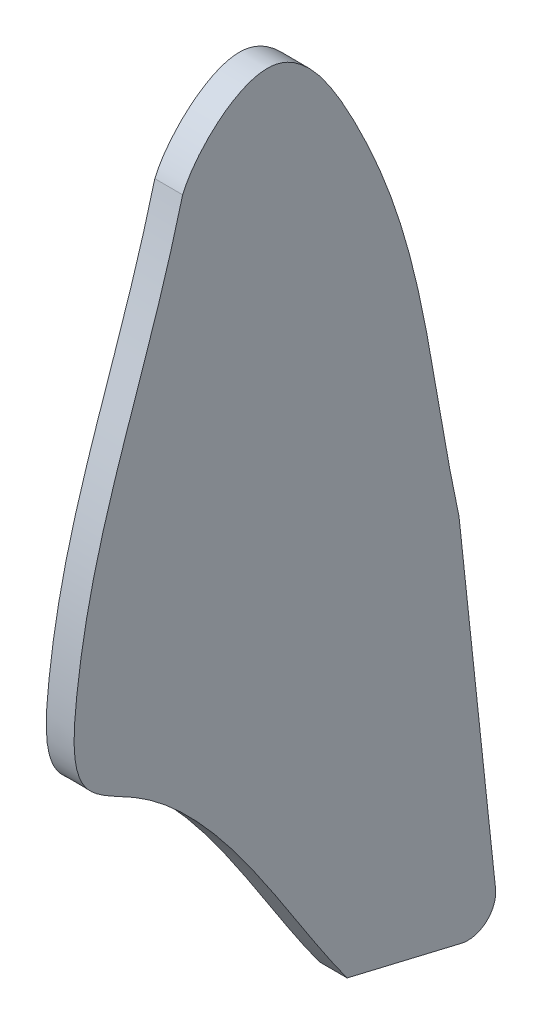
SolidWorks part; units mm, degrees
material "Plain Carbon Steel"
ref_plane "Front Plane" through (0, 0, 0) normal (0, 0, 1) x (1, 0, 0)
ref_plane "Top Plane" through (0, 0, 0) normal (0, 1, 0) x (1, 0, 0)
ref_plane "Right Plane" through (0, 0, 0) normal (1, 0, 0) x (0, 0, -1)
sketch "Sketch4" plane through (14.4103, -0.0874, -0.0186) normal (1, -0.0061, -0.0013) x (-0.0013, 0, -1)
  line L0 (-673.2339, -268.4398) -> (-669.6973, -299.797)
  line L1 (-672.8126, -302.5518) -> (-683.2896, -300.0438)
  arc A0 (-672.8126, -302.5518) -> (-669.6973, -299.797) centre (-672.2213, -300.0816) ccw
  spline S9 degree 3 poles (-698.7775, -230.0458) (-702.2395, -243.821) (-707.9176, -253.9744) (-708.8071, -273.0765) (-702.4475, -275.7749) (-693.2362, -283.5609) (-688.1132, -293.4424) (-683.2896, -300.0438) knots 0 0 0 0 0.455994 0.548053 0.607594 0.690344 1 1 1 1
  spline S10 degree 3 poles (-698.7775, -230.0458) (-698.9283, -230.4835) (-699.1754, -231.201) (-699.4694, -232.0631) (-699.6662, -232.6425) (-699.8841, -233.2862) (-700.1658, -234.1231) (-700.6571, -235.5947) (-701.2591, -237.4232) (-701.9995, -239.7184) (-702.7796, -242.1932) (-703.5373, -244.6722) (-704.2802, -247.1887) (-704.8879, -249.3249) (-705.4374, -251.3379) (-705.7977, -252.7112) (-706.0688, -253.7768) (-706.3003, -254.7057) (-706.5816, -255.8735) (-706.8259, -256.9376) (-706.993, -257.6938) (-707.0952, -258.1664) (-707.1887, -258.6079) (-707.2783, -259.041) (-707.3639, -259.4642) (-707.4445, -259.8718) (-707.5213, -260.2706) (-707.5928, -260.6512) (-707.6849, -261.1542) (-707.8016, -261.8198) (-707.9271, -262.5888) (-708.0392, -263.3334) (-708.139, -264.058) (-708.2271, -264.776) (-708.3035, -265.4969) (-708.3617, -266.1575) (-708.4044, -266.778) (-708.433, -267.3589) (-708.4482, -267.9088) (-708.45, -268.4528) (-708.4394, -268.9094) (-708.4179, -269.3515) (-708.3801, -269.8533) (-708.3156, -270.3819) (-708.2248, -270.8846) (-708.1288, -271.2949) (-708.0038, -271.7075) (-707.8471, -272.1036) (-707.6639, -272.4576) (-707.4972, -272.7052) (-707.3621, -272.8716) (-707.2613, -272.9816) (-707.1527, -273.0862) (-707.065, -273.1599) (-707.0006, -273.2092) (-706.9642, -273.2359) (-706.9293, -273.2603) (-706.8957, -273.2828) (-706.8644, -273.303) (-706.8257, -273.3267) (-706.7839, -273.352) (-706.7398, -273.379) (-706.6789, -273.4161) (-706.605, -273.4612) (-706.5197, -273.5135) (-706.4446, -273.5597) (-706.3751, -273.6025) (-706.306, -273.6452) (-706.2327, -273.6906) (-706.1543, -273.7392) (-706.0373, -273.8121) (-705.8835, -273.9083) (-705.7009, -274.0233) (-705.5354, -274.1282) (-705.3072, -274.2738) (-705.0117, -274.464) (-704.6924, -274.6724) (-704.3994, -274.8659) (-704.1543, -275.0294) (-703.8824, -275.2126) (-703.5884, -275.4128) (-703.2651, -275.636) (-702.9253, -275.8739) (-702.5958, -276.1077) (-702.2571, -276.3518) (-701.9184, -276.5994) (-701.5649, -276.8619) (-701.1766, -277.155) (-700.7791, -277.4608) (-700.4311, -277.7339) (-700.1646, -277.9462) (-699.9449, -278.1229) (-699.7183, -278.3073) (-699.5011, -278.4862) (-699.2866, -278.6647) (-699.0413, -278.8711) (-698.7742, -279.0992) (-698.5025, -279.3349) (-698.2462, -279.5602) (-697.9841, -279.7942) (-697.7218, -280.0319) (-697.4555, -280.277) (-697.1909, -280.5247) (-696.9213, -280.7812) (-696.6601, -281.034) (-696.4161, -281.2744) (-696.1841, -281.5064) (-695.8916, -281.8037) (-695.5234, -282.1871) (-695.072, -282.6727) (-694.6128, -283.186) (-694.124, -283.756) (-693.6199, -284.3723) (-693.1153, -285.0263) (-692.6259, -285.7016) (-692.2313, -286.2845) (-691.9097, -286.7907) (-691.6682, -287.1904) (-691.4564, -287.5588) (-691.2769, -287.8875) (-691.1481, -288.1334) (-691.0573, -288.3143) (-690.9724, -288.4648) (-690.8754, -288.63) (-690.7665, -288.8104) (-690.646, -289.0065) (-690.5134, -289.2194) (-690.2325, -289.6655) (-689.8417, -290.2748) (-689.2843, -291.1335) (-688.6418, -292.1145) (-687.8145, -293.3681) (-686.8933, -294.757) (-685.9984, -296.0951) (-685.1225, -297.3887) (-684.2093, -298.7222) (-683.1938, -300.1846) (-682.0014, -301.876) (-680.7046, -303.6813) (-679.3728, -305.4954) (-678.0605, -307.2476) (-676.863, -308.8129) (-675.787, -310.19) (-675.01, -311.1689) (-674.3487, -311.9921) (-673.7051, -312.7845) (-672.8128, -313.8687) (-671.7483, -315.1375) (-670.3799, -316.7286) (-669.0401, -318.2418) (-667.805, -319.5931) (-666.6121, -320.8681) (-665.1975, -322.3333) (-663.7479, -323.8527) (-662.4585, -325.2109) (-661.4906, -326.2361) (-660.6233, -327.1596) (-659.8432, -327.9946) (-659.0429, -328.8559) (-658.3429, -329.6156) (-657.7937, -330.2176) (-657.4469, -330.6009) (-657.1396, -330.944) (-656.873, -331.2455) (-656.6439, -331.5122) (-656.4168, -331.7662) (-656.176, -332.0259) (-655.9123, -332.2988) (-655.6226, -332.5856) (-655.3055, -332.8846) (-654.9601, -333.1933) (-654.2935, -333.7557) (-653.3752, -334.4331) (-652.3324, -335.0636) (-651.4997, -335.499) (-650.7441, -335.85) (-650.055, -336.125) (-649.508, -336.3171) (-649.1569, -336.4314) (-648.8179, -336.534) (-648.5369, -336.6127) (-648.2928, -336.6767) (-648.088, -336.7278) (-647.8602, -336.7812) (-647.6214, -336.8334) (-647.3919, -336.8798) (-647.1889, -336.9179) (-647.0175, -336.9478) (-646.8801, -336.9702) (-646.7476, -336.9905) (-646.6034, -337.0113) (-646.4301, -337.034) (-646.2347, -337.0571) (-646.1027, -337.0701) (-646.0343, -337.0769) knots 0 0 0 0 0.010354 0.016974 0.020418 0.02403 0.032152 0.040132 0.058626 0.075011 0.093721 0.116164 0.132367 0.151695 0.165154 0.178372 0.182964 0.189313 0.199358 0.209279 0.213243 0.216296 0.219824 0.222994 0.225789 0.228961 0.231851 0.234458 0.237211 0.242731 0.248828 0.253752 0.258677 0.264309 0.269025 0.273961 0.278275 0.282099 0.286182 0.289822 0.293516 0.295769 0.299123 0.304111 0.307008 0.310024 0.313198 0.316487 0.319629 0.322583 0.323893 0.325222 0.326612 0.328109 0.328575 0.329002 0.329393 0.329748 0.330066 0.330363 0.330691 0.331092 0.33159 0.332654 0.333606 0.334447 0.33519 0.33596 0.336787 0.337672 0.338614 0.340749 0.342889 0.34484 0.346408 0.350671 0.354893 0.357369 0.360757 0.363256 0.366715 0.370783 0.374289 0.378263 0.38191 0.385725 0.389571 0.393705 0.398489 0.402645 0.404986 0.407064 0.40973 0.412188 0.413952 0.416544 0.419873 0.422302 0.425033 0.427786 0.430372 0.433118 0.435919 0.438446 0.441356 0.443856 0.445873 0.448444 0.452783 0.457175 0.46242 0.467232 0.472942 0.479203 0.484837 0.491191 0.495092 0.498804 0.502328 0.50549 0.508191 0.509408 0.510763 0.512213 0.513746 0.515435 0.51726 0.519205 0.526844 0.532773 0.541044 0.551767 0.564616 0.5763 0.585801 0.597649 0.610475 0.623445 0.641406 0.65747 0.671031 0.68768 0.699119 0.707955 0.714085 0.721413 0.729507 0.743745 0.756399 0.773833 0.786394 0.79504 0.810678 0.829373 0.839402 0.850283 0.859276 0.866326 0.874645 0.884485 0.888625 0.892442 0.895904 0.898979 0.901704 0.904441 0.90731 0.910414 0.913752 0.917319 0.921114 0.925132 0.938769 0.949132 0.954719 0.961286 0.969061 0.972373 0.975164 0.977805 0.980702 0.982162 0.983794 0.985603 0.987584 0.989487 0.991131 0.992517 0.993654 0.994493 0.995577 0.996889 0.998388 1 1 1 1 construction
  spline S11 degree 3 poles (-712.7374, -275.3552) (-712.6373, -275.3587) (-712.4708, -275.3644) (-712.2466, -275.3724) (-712.0219, -275.3805) (-711.7624, -275.39) (-711.3586, -275.4051) (-710.824, -275.4254) (-710.1504, -275.4513) (-709.4831, -275.4766) (-708.8222, -275.5012) (-708.1209, -275.5264) (-707.4081, -275.5506) (-706.7724, -275.5707) (-706.2699, -275.5855) (-705.7516, -275.5999) (-705.0966, -275.6164) (-704.3062, -275.6334) (-703.6223, -275.645) (-703.0739, -275.6523) (-702.6623, -275.6568) (-702.2522, -275.6602) (-701.8393, -275.6625) (-701.4453, -275.6636) (-701.0236, -275.6635) (-700.6016, -275.6622) (-700.1612, -275.6594) (-699.7237, -275.6551) (-699.2905, -275.6493) (-698.8543, -275.6418) (-698.3823, -275.6321) (-697.8824, -275.6195) (-697.3882, -275.6047) (-696.927, -275.5888) (-696.4865, -275.5718) (-696.0462, -275.5528) (-695.6167, -275.5323) (-695.1997, -275.5105) (-694.7764, -275.4865) (-694.332, -275.4591) (-693.672, -275.4148) (-692.7998, -275.3483) (-691.7381, -275.2526) (-690.7675, -275.1506) (-689.9491, -275.0533) (-689.243, -274.9613) (-688.5651, -274.8654) (-687.8722, -274.7586) (-687.1706, -274.6413) (-686.4941, -274.5187) (-685.6035, -274.3444) (-684.7403, -274.1563) (-683.8745, -273.9459) (-683.2362, -273.7793) (-682.5996, -273.6013) (-682.0391, -273.4332) (-681.548, -273.2771) (-681.1193, -273.1343) (-680.7714, -273.0127) (-680.5061, -272.9165) (-680.3325, -272.8524) (-680.1473, -272.7826) (-679.9507, -272.7069) (-679.8171, -272.654) (-679.7481, -272.6266) knots 0 0 0 0 0.011538 0.01919 0.026519 0.037429 0.048574 0.071659 0.095904 0.120228 0.140846 0.162884 0.189986 0.210375 0.223875 0.23759 0.259216 0.284854 0.310438 0.32146 0.334507 0.347438 0.358302 0.371396 0.38251 0.39578 0.408679 0.421428 0.434153 0.446745 0.459608 0.475418 0.490244 0.502614 0.515413 0.528434 0.540683 0.55255 0.564391 0.577206 0.590804 0.6212 0.652155 0.68194 0.704474 0.722364 0.742566 0.762665 0.781963 0.802929 0.821021 0.858897 0.87778 0.89646 0.914739 0.933703 0.945952 0.958324 0.971918 0.976714 0.981917 0.987531 0.993558 1 1 1 1 construction
  spline S12 degree 3 poles (-698.7775, -230.0458) (-697.6813, -227.3643) (-690.2062, -220.1338) (-676.3929, -241.8534) (-676.2659, -254.7469) (-673.2339, -268.4398) knots 0 0 0 0 0.170249 0.356058 1 1 1 1
  spline S13 degree 2 poles (-646.0342, -337.0291) (-644.31, -335.9334) (-655.4996, -317.2396) (-660.531, -304.2192) (-671.2828, -283.317) (-677.9007, -231.3122) (-693.9097, -221.7096) (-698.7775, -230.0458) knots -1.570796 -1.570796 -1.570796 -0.741778 -0.455848 -0.116901 0 1.052205 1.570796 1.570796 1.570796 weights 1 0.896947 0.831497 0.808955 0.804738 0.804738 0.935535 1 construction
  spline S14 degree 3 poles (-653.9964, -319.6086) (-654.0117, -319.5802) (-654.0407, -319.5263) (-654.0854, -319.443) (-654.1283, -319.3631) (-654.1695, -319.2859) (-654.2095, -319.2105) (-654.2491, -319.1353) (-654.2902, -319.0572) (-654.3343, -318.9729) (-654.3817, -318.8823) (-654.4322, -318.7851) (-654.4859, -318.6816) (-654.5426, -318.5715) (-654.6025, -318.4549) (-654.6655, -318.3317) (-654.7315, -318.202) (-654.8408, -317.9859) (-654.9851, -317.6977) (-655.1558, -317.3517) (-655.3061, -317.043) (-655.4385, -316.7678) (-655.5629, -316.5066) (-655.6909, -316.2354) (-655.8301, -315.9371) (-655.9983, -315.5722) (-656.1865, -315.1573) (-656.3855, -314.7105) (-656.5684, -314.2927) (-656.7497, -313.8721) (-656.9383, -313.4268) (-657.2137, -312.7641) (-657.501, -312.0531) (-657.7706, -311.3574) (-657.9703, -310.8462) (-658.2488, -310.1506) (-658.6456, -309.1889) (-659.176, -307.9481) (-659.7619, -306.6169) (-660.4036, -305.1954) (-661.097, -303.6921) (-661.9374, -301.9044) (-663.1319, -299.4127) (-664.7577, -296.1009) (-666.3239, -292.9833) (-667.5427, -290.5872) (-668.2908, -289.129) (-668.9021, -287.9349) (-669.4264, -286.8105) (-669.8755, -285.7669) (-670.2535, -284.7979) (-670.5586, -283.9495) (-670.8123, -283.183) (-671.0791, -282.2969) (-671.2857, -281.5236) (-671.4549, -280.8083) (-671.5602, -280.319) (-671.6449, -279.8869) (-671.7094, -279.5314) (-671.7579, -279.2409) (-671.7941, -279.0088) (-671.8201, -278.8332) (-671.8444, -278.661) (-671.8682, -278.483) (-671.8916, -278.2943) (-671.9241, -278.0267) (-671.9651, -277.6937) (-672.0129, -277.307) (-672.061, -276.9222) (-672.1129, -276.5096) (-672.1724, -276.0417) (-672.2664, -275.3095) (-672.3803, -274.4399) (-672.5797, -272.9526) (-672.8752, -270.8294) (-673.3976, -267.3124) (-674.0774, -263.1683) (-674.6851, -259.8828) (-675.0389, -258.0915) (-675.1548, -257.5134) (-675.4165, -256.2285) (-675.7212, -254.797) (-676.0613, -253.2793) (-676.3032, -252.2282) (-676.5766, -251.0758) (-676.9413, -249.5951) (-677.3358, -248.067) (-677.7646, -246.4866) (-678.1112, -245.2654) (-678.4079, -244.2578) (-678.6357, -243.5037) (-678.8637, -242.7671) (-679.1572, -241.8422) (-679.5034, -240.7892) (-679.8186, -239.8716) (-680.0335, -239.2626) (-680.1574, -238.9162) (-680.2566, -238.6427) (-680.3266, -238.4512) (-680.3796, -238.307) (-680.4395, -238.1448) (-680.5074, -237.9625) (-680.583, -237.7611) (-680.6671, -237.5386) (-680.7259, -237.3849) (-680.7568, -237.304) knots 0 0 0 0 0.001455 0.002764 0.003939 0.004997 0.005965 0.006898 0.007903 0.008989 0.010157 0.011407 0.012739 0.014153 0.015649 0.017229 0.018891 0.020637 0.025524 0.029929 0.033851 0.037288 0.040404 0.043809 0.047567 0.051683 0.057571 0.063171 0.068439 0.073192 0.078857 0.085003 0.097774 0.10512 0.110557 0.116572 0.130782 0.146188 0.162791 0.180596 0.199603 0.219495 0.248252 0.294247 0.345853 0.367744 0.38632 0.40199 0.413684 0.428807 0.440897 0.449315 0.459716 0.468573 0.481063 0.487242 0.493963 0.498429 0.502585 0.506627 0.508803 0.510902 0.512934 0.515033 0.517247 0.519583 0.524378 0.528838 0.533037 0.537739 0.543156 0.549274 0.563149 0.573342 0.60087 0.636764 0.695255 0.744787 0.751145 0.75782 0.764989 0.796078 0.807999 0.818346 0.833113 0.84869 0.870777 0.887465 0.905183 0.914652 0.923843 0.932485 0.941431 0.957566 0.971106 0.975316 0.980179 0.983986 0.985555 0.987336 0.98933 0.99155 0.994062 0.996877 1 1 1 1 construction
  spline S15 degree 2 poles (-715.0854, -274.4692) (-678.2084, -278.6383) (-656.4552, -238.2207) (-658.9196, -190.013) (-684.1553, -184.6496) knots 0 0 0 0.291765 0.847897 1.570796 1.570796 1.570796 weights 1 0.945597 0.846229 0.865207 1 construction
  spline S16 degree 2 poles (-698.7775, -230.0458) (-695.7175, -230.228) (-686.6215, -257.8591) (-677.1616, -287.3469) (-668.0975, -306.5984) (-655.6906, -325.7547) (-645.7482, -337.7151) (-646.0342, -337.0291) knots -1.570796 -1.570796 -1.570796 -1.052205 0 0.116901 0.455848 0.741778 1.570796 1.570796 1.570796 weights 1 0.935535 0.804738 0.804738 0.808955 0.831497 0.896947 1 construction
  point P18 (-669.2915, -303.3947)
  dimension "D1" = 2.54
extrude "Boss-Extrude1" add sketch "Sketch4" along normal blind 2.54
sketch "Sketch5" plane through (16.9503, -0.1028, -0.0219) normal (1, -0.0061, -0.0013) x (-0.0013, 0, -1)
  circle A0 centre (-690.8949, -231.7002) radius 0.254
